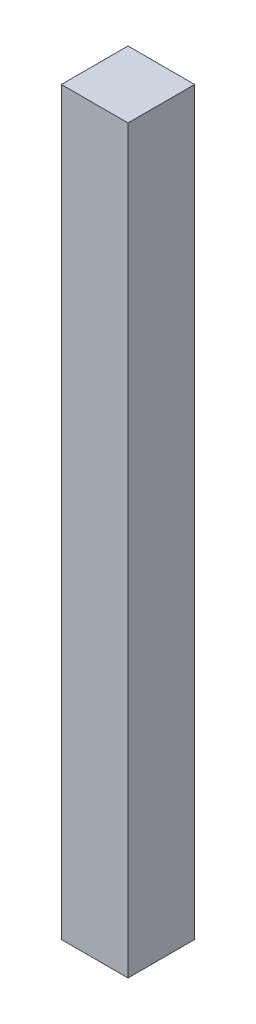
SolidWorks part; units mm, degrees
ref_plane "Front Plane" through (0, 0, 0) normal (0, 0, 1) x (1, 0, 0)
ref_plane "Top Plane" through (0, 0, 0) normal (0, 1, 0) x (1, 0, 0)
ref_plane "Right Plane" through (0, 0, 0) normal (1, 0, 0) x (0, 0, -1)
other "Configuration Table"
sketch "Sketch1" plane through (0, 0, 0) normal (0, 0, 1) x (1, 0, 0)
  line L1 (45, 1590) -> (63, 1590)
  line L2 (45, 1590) -> (45, 1790)
  line L3 (45, 1790) -> (63, 1790)
  line L4 (63, 1590) -> (63, 1790)
extrude "TOPPING_klape_kat1_gazli_amortisor_1_1" add sketch "Sketch1" along normal blind 18 from offset 8 separate body
